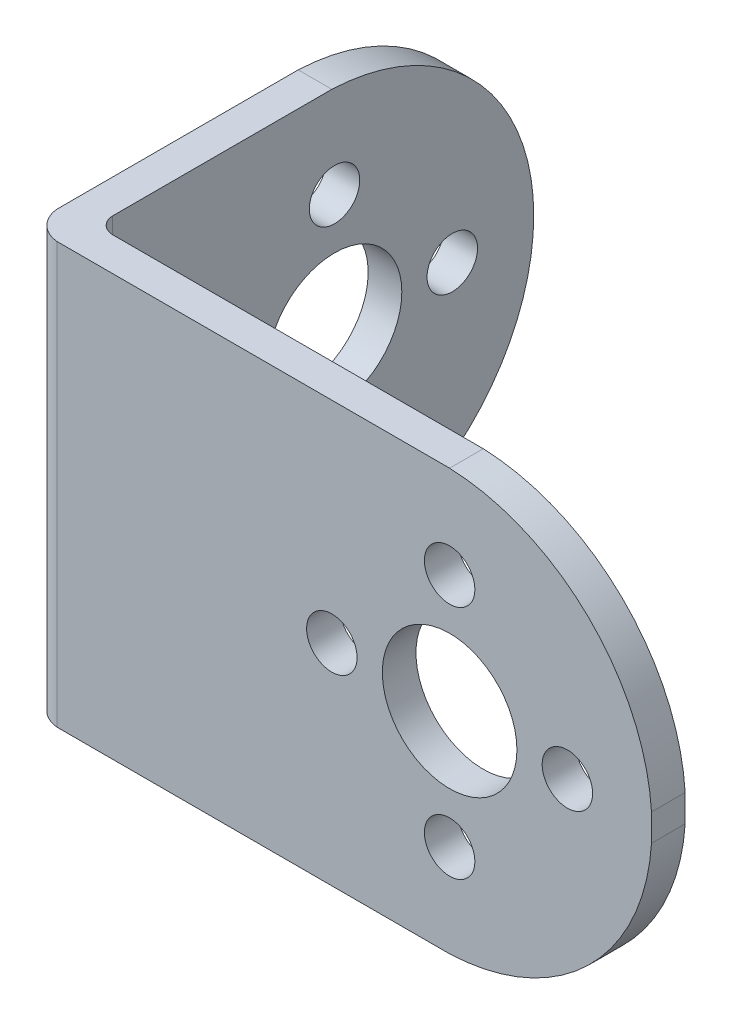
SolidWorks part; units mm, degrees
material "1060 Alloy"
ref_plane "Front Plane" through (0, 0, 0) normal (0, 0, 1) x (1, 0, 0)
ref_plane "Top Plane" through (0, 0, 0) normal (0, 1, 0) x (1, 0, 0)
ref_plane "Right Plane" through (0, 0, 0) normal (1, 0, 0) x (0, 0, -1)
sketch "Sketch1" plane through (0, 0, 0) normal (0, 1, 0) x (1, 0, 0)
  line L0 (1.6591, 0) -> (37, 0)
  line L1 (37, 0) -> (37, 2)
  line L2 (37, 2) -> (2.9676, 2)
  line L3 (0, 2) -> (0, 1.6591)
  line L4 (0, 1.6591) -> (0, 28)
  line L5 (0, 28) -> (2, 28)
  line L6 (2, 28) -> (2, 2.9676)
  arc A0 (0, 2) -> (2, 0) centre (1.8295, 1.8295) ccw
  arc A1 (2, 2.9676) -> (3.0387, 2) centre (3.0031, 3.0031) ccw
  dimension "D1" = 2
extrude "Boss-Extrude1" add sketch "Sketch1" along normal blind 25 contours A1 L6 L5 L4 L3 A0 L0 L1 L2
sketch "Sketch2" plane through (0, 0, 0) normal (-1, 0, 0) x (0, 0, 1)
  line L0 (-28, 12.5) -> (-16, 12.5) construction
  line L1 (-28, 25) -> (-28, 0) construction
  line L2 (-1.6591, 0) -> (-28, 0) construction
  line L3 (-1.6591, 25) -> (-28, 25) construction
  line L4 (-16, 25) -> (-28, 25)
  line L5 (-28, 25) -> (-28, 12.5)
  line L6 (-28, 12.5) -> (-28, 0)
  line L7 (-28, 0) -> (-16, 0)
  arc A0 (-16, 0) -> (-16, 25) centre (-15.4896, 12.5) cw
  line M3 (-28, 0) -> (-1.6591, 0)
  line M5 (-1.6591, 25) -> (-28, 25)
  line M6 (-28, 25) -> (-28, 0)
  dimension "D1" = 12
extrude "Cut-Extrude1" cut sketch "Sketch2" against normal blind 25 contours A0 M6 M5 | A0 M3 M6
sketch "Sketch4" plane through (0, 0, 0) normal (0, 0, 1) x (1, 0, 0)
  line L0 (37, 12.5) -> (25, 12.5) construction
  line L1 (37, 25) -> (37, 0) construction
  line L2 (1.6591, 0) -> (37, 0) construction
  line L3 (1.6591, 25) -> (37, 25) construction
  line L4 (25, 25) -> (37, 25)
  line L5 (37, 25) -> (37, 12.5)
  line L6 (37, 12.5) -> (37, 0)
  line L7 (37, 0) -> (25, 0)
  line L8 (25, 12.5) -> (25, 19.5) construction
  circle A0 centre (25, 12.5) radius 4
  arc A1 (25, 0) -> (25, 25) centre (24.5166, 12.5) ccw
  circle A2 centre (25, 19.5) radius 1.5
  circle A3 centre (32, 12.5) radius 1.5
  circle A4 centre (25, 5.5) radius 1.5
  circle A5 centre (18, 12.5) radius 1.5
  point P27 (25, 12.5)
  line M1 (1.6591, 0) -> (37, 0)
  line M2 (37, 0) -> (37, 25)
  line M3 (37, 25) -> (1.6591, 25)
  dimension "D1" = 3
  dimension "D2" = 4
extrude "Cut-Extrude2" cut sketch "Sketch4" against normal blind 25 contours A1 L5 M3 | A1 M1 M2
sketch "Sketch5" plane through (0, 0, 0) normal (0, 0, 1) x (1, 0, 0)
  line L0 (37, 12.5) -> (25, 12.5) construction
  line L1 (37, 13.3055) -> (37, 11.6945) construction
  line L2 (25, 12.5) -> (25, 19.5) construction
  circle A0 centre (25, 12.5) radius 4
  circle A5 centre (25, 19.5) radius 1.5
  circle A6 centre (32, 12.5) radius 1.5
  circle A7 centre (25, 5.5) radius 1.5
  circle A8 centre (18, 12.5) radius 1.5
  point P16 (25, 12.5)
  point P17 (25, 12.5)
  dimension "D1" = 7
  dimension "D2" = 4
extrude "Cut-Extrude3" cut sketch "Sketch5" against normal blind 25
sketch "Sketch6" plane through (0, 0, 0) normal (-1, 0, 0) x (0, 0, 1)
  line L0 (-28, 12.5) -> (-16.1591, 12.5) construction
  line L1 (-16.1591, 12.5) -> (-16.1591, 5.5) construction
  line L2 (-1.6591, 25) -> (-1.6591, 0) construction
  arc A0 (-16, 25) -> (-16, 0) centre (-15.4896, 12.5) ccw construction
  circle A1 centre (-16.1591, 12.5) radius 4
  circle A7 centre (-16.1591, 19.5) radius 1.5
  circle A10 centre (-9.1591, 12.5) radius 1.5
  circle A11 centre (-16.1591, 5.5) radius 1.5
  circle A12 centre (-23.1591, 12.5) radius 1.5
  point P7 (0, 0)
  point P9 (0, 0)
  point P12 (-9.341, 12.4852)
  point P18 (-16, 12.5)
  point P25 (-16.1591, 12.5)
  dimension "D1" = 7
  dimension "D2" = 4
  dimension "D3" = 7
  dimension "D4" = 3
  dimension "D5" = 8
  dimension "D6" = 7
  dimension "D7" = 7
  dimension "D8" = 14.5
extrude "Cut-Extrude4" cut sketch "Sketch6" against normal blind 25
